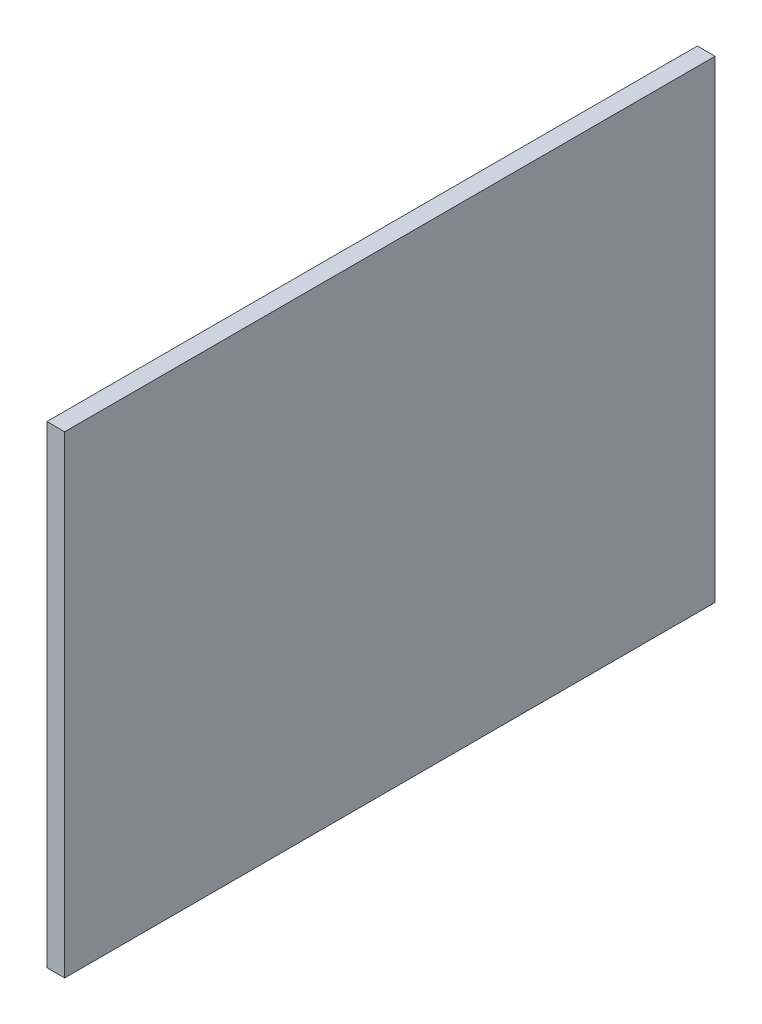
SolidWorks part; units mm, degrees
ref_plane "Front" through (0, 0, 0) normal (0, 0, 1) x (1, 0, 0)
ref_plane "Top" through (0, 0, 0) normal (0, 1, 0) x (1, 0, 0)
ref_plane "Right" through (0, 0, 0) normal (1, 0, 0) x (0, 0, -1)
sketch "Sketch1" plane through (0, 0, 0) normal (1, 0, 0) x (0, 0, -1)
  line L1 (-36.2025, 17.2235) -> (73.7975, 17.2235)
  line L2 (-36.2025, 17.2235) -> (-36.2025, -62.7765)
  line L3 (-36.2025, -62.7765) -> (73.7975, -62.7765)
  line L4 (73.7975, 17.2235) -> (73.7975, -62.7765)
  dimension "D1" = 110
  dimension "D2" = 80
extrude "Boss-Extrude1" add sketch "Sketch1" along normal blind 3 contours L2 L1 L4 L3
